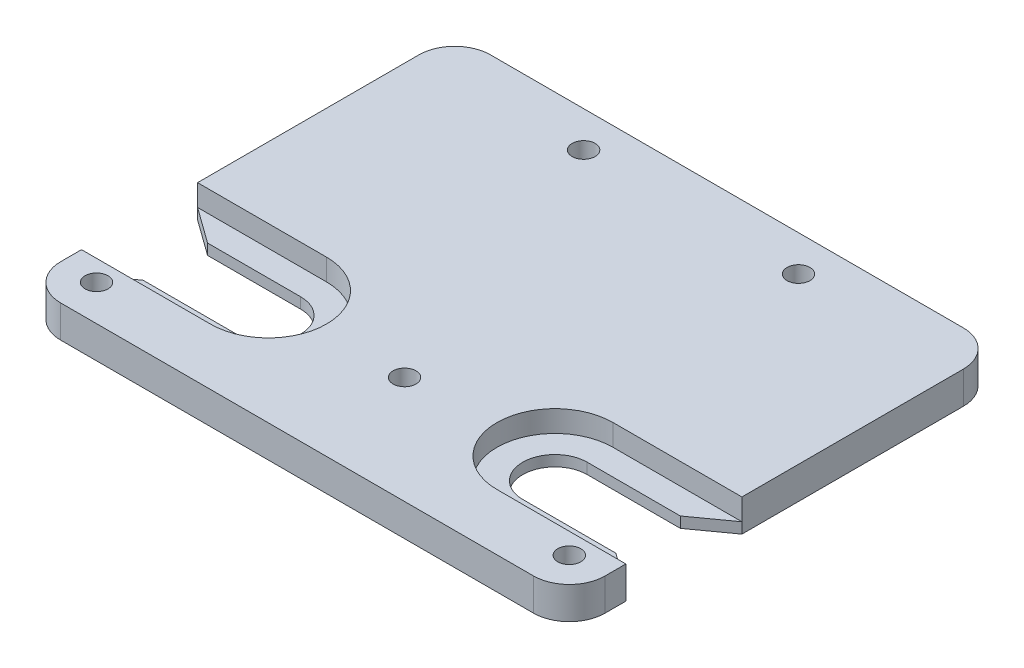
SolidWorks part; units mm, degrees
material "ABS"
ref_plane "Front Plane" through (0, 0, 0) normal (0, 0, 1) x (1, 0, 0)
ref_plane "Top Plane" through (0, 0, 0) normal (0, 1, 0) x (1, 0, 0)
ref_plane "Right Plane" through (0, 0, 0) normal (1, 0, 0) x (0, 0, -1)
sketch "Sketch1" plane through (0, 0, 0) normal (0, 1, 0) x (1, 0, 0)
  line L1 (-38, -30) -> (38, -30)
  line L2 (-38, -30) -> (-38, 30)
  line L3 (-38, 30) -> (38, 30)
  line L4 (38, -30) -> (38, 30)
  line L5 (-38, -30) -> (38, 30) construction
  line L6 (-38, 30) -> (38, -30) construction
  point P0 (0, 0)
  dimension "D1" = 60
  dimension "D2" = 76
extrude "Boss-Extrude1" add sketch "Sketch1" along normal blind 4.5
sketch "Sketch2" plane through (0, 4.5, 0) normal (0, 1, 0) x (1, 0, 0)
  line L0 (-38, -14) -> (-20, -14) construction
  line L1 (-38, 30) -> (-38, -30) construction
  line L2 (-20, -14) -> (0, -14) construction
  line L3 (0, -14) -> (20, -14) construction
  line L4 (20, -14) -> (38, -14) construction
  line L5 (38, -30) -> (38, 30) construction
  line L6 (0, 0) -> (0, -14) construction
  line L7 (20, -5.9) -> (38, -5.9)
  line L8 (20, -22.1) -> (38, -22.1)
  line L9 (-38, -30) -> (38, -30) construction
  line L10 (38, -5.9) -> (38, -22.1)
  arc A0 (20, -5.9) -> (20, -22.1) centre (20, -14) ccw
  dimension "D2" = 16.2
  dimension "D1" = 40
  dimension "D3" = 16
extrude "Cut-Extrude1" cut sketch "Sketch2" against normal offset from surface (3 mm away) 1.5 up to face at (0, 0, 0)
sketch "Sketch3" plane through (0, 1.5, 0) normal (0, 1, 0) x (1, 0, 0)
  line L0 (20, -9.5) -> (33, -9.5)
  line L1 (33, -9.5) -> (38, -5.9)
  line L2 (38, -5.9) -> (38, -22.1)
  line L3 (38, -22.1) -> (33, -18.5)
  line L4 (33, -18.5) -> (20, -18.5)
  line L5 (33, -9.5) -> (33, -18.5) construction
  arc A0 (20, -9.5) -> (20, -18.5) centre (20, -14) ccw
  dimension "D1" = 9
  dimension "D2" = 5
extrude "Cut-Extrude2" cut sketch "Sketch3" against normal through all
mirror "Mirror1" about plane through (0, 0, 0) normal (1, 0, 0) of "Cut-Extrude2", "Cut-Extrude1"
fillet "Fillet1" radius 5 4 edges at (-38, 2.25, -30) (38, 2.25, -30) (-38, 2.25, 30) (38, 2.25, 30)
sketch "Sketch4" plane through (0, 4.5, 0) normal (0, 1, 0) x (1, 0, 0)
  line L0 (0, 30) -> (0, 15) construction
  line L1 (33, 30) -> (-33, 30) construction
  line L2 (0, 15) -> (0, -15) construction
  line L3 (0, -15) -> (0, -30) construction
  line L4 (-33, -30) -> (33, -30) construction
  line L5 (-33, 25) -> (-15, 25) construction
  line L6 (-15, 25) -> (15, 25) construction
  line L7 (15, 25) -> (33, 25) construction
  circle A0 centre (-15, 25) radius 1.6
  circle A1 centre (15, 25) radius 1.6
  circle A2 centre (33, -25) radius 1.6
  circle A3 centre (-33, -25) radius 1.6
  circle A5 centre (0, -15) radius 1.6
  dimension "D1" = 3.2
  dimension "D2" = 15
  dimension "D3" = 30
extrude "Cut-Extrude3" cut sketch "Sketch4" against normal through all
chamfer "Chamfer1" [suppressed] distance 1 distance2 1
